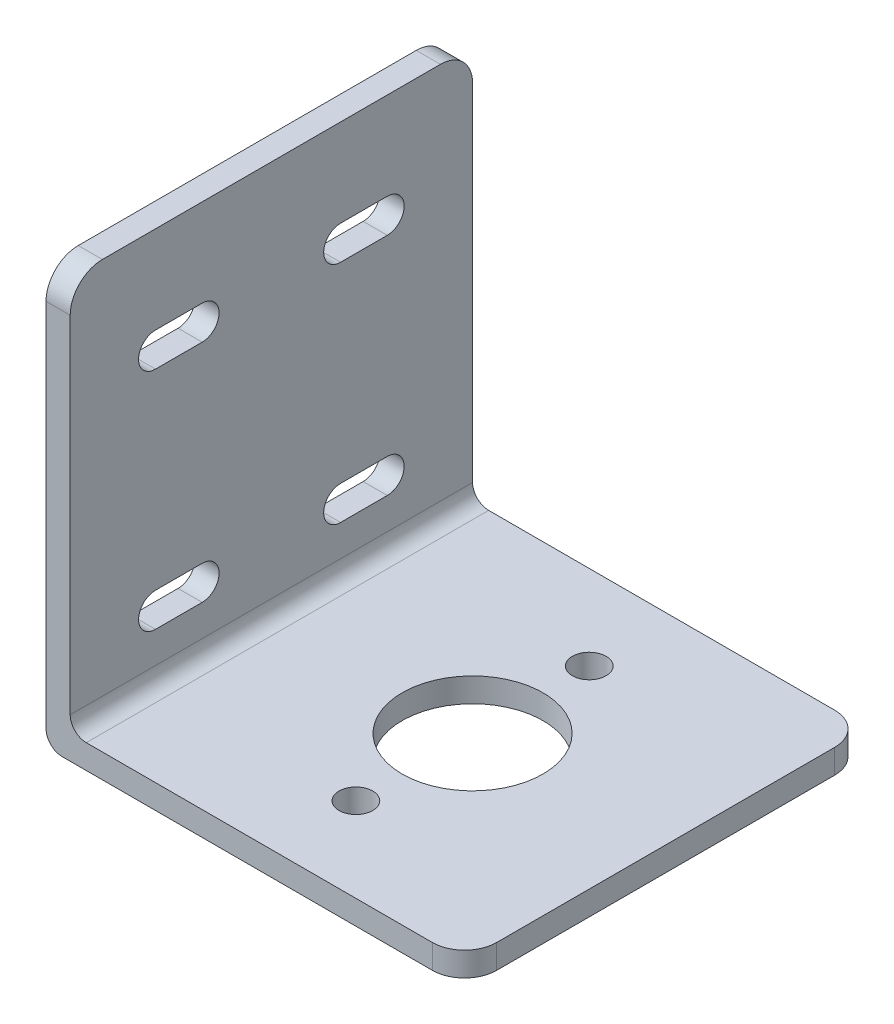
SolidWorks part; units mm, degrees
ref_plane "Спереди" through (0, 0, 0) normal (0, 0, 1) x (1, 0, 0)
ref_plane "Сверху" through (0, 0, 0) normal (0, 1, 0) x (1, 0, 0)
ref_plane "Справа" through (0, 0, 0) normal (1, 0, 0) x (0, 0, -1)
sketch "Эскиз1" plane through (0, 0, 0) normal (0, 1, 0) x (1, 0, 0)
  line L0 (28, 50) -> (28, 0) construction
  line L1 (0, 0) -> (52, 0)
  line L2 (0, 0) -> (0, 50)
  line L3 (0, 50) -> (52, 50)
  line L4 (52, 0) -> (52, 50)
  circle A0 centre (28, 39.5) radius 2.1
  circle A1 centre (28, 10.5) radius 2.1
  circle A2 centre (28, 25) radius 8.75
  dimension "D6" = 17.5
  dimension "D7" = 4.2
  dimension "D8" = 4.2
  dimension "D1" = 50
  dimension "D2" = 52
  dimension "D3" = 28
  dimension "D4" = 29
  dimension "D5" = 14.5
extrude "Бобышка-Вытянуть1" add sketch "Эскиз1" along normal blind 3
sketch "Эскиз2" plane through (0, 3, 0) normal (0, 1, 0) x (1, 0, 0)
  line L0 (0, 0) -> (52, 0) construction
  line L1 (0, 50) -> (3, 50)
  line L2 (0, 50) -> (0, 0)
  line L3 (0, 0) -> (3, 0)
  line L4 (3, 50) -> (3, 0)
  dimension "D1" = 3
extrude "Бобышка-Вытянуть2" add sketch "Эскиз2" along normal blind 49
sketch "Эскиз3" plane through (0, 0, 0) normal (-1, 0, 0) x (0, 0, 1)
  line L0 (-50, 39) -> (0, 39) construction
  line L1 (-50, 52) -> (-50, 0) construction
  line L2 (0, 52) -> (0, 0) construction
  line L3 (-50, 11) -> (0, 11) construction
  line L4 (-50, 0) -> (0, 0) construction
  line L5 (-36.5, 13.1) -> (-36.5, 8.9) construction
  line L6 (-39.4, 13.1) -> (-33.6, 13.1)
  line L7 (-16.4, 13.1) -> (-10.6, 13.1)
  line L8 (-39.4, 8.9) -> (-33.6, 8.9)
  line L9 (-16.4, 8.9) -> (-10.6, 8.9)
  line L10 (-16.4, 41.1) -> (-10.6, 41.1)
  line L11 (-16.4, 36.9) -> (-10.6, 36.9)
  line L12 (-39.4, 41.1) -> (-33.6, 41.1)
  line L13 (-39.4, 36.9) -> (-33.6, 36.9)
  line L14 (-13.5, 13.1) -> (-13.5, 8.9) construction
  arc A0 (-39.4, 13.1) -> (-39.4, 8.9) centre (-39.4, 11) ccw
  arc A1 (-33.6, 8.9) -> (-33.6, 13.1) centre (-33.6, 11) ccw
  arc A2 (-16.4, 13.1) -> (-16.4, 8.9) centre (-16.4, 11) ccw
  arc A3 (-10.6, 8.9) -> (-10.6, 13.1) centre (-10.6, 11) ccw
  arc A4 (-16.4, 41.1) -> (-16.4, 36.9) centre (-16.4, 39) ccw
  arc A5 (-10.6, 36.9) -> (-10.6, 41.1) centre (-10.6, 39) ccw
  arc A6 (-39.4, 41.1) -> (-39.4, 36.9) centre (-39.4, 39) ccw
  arc A7 (-33.6, 36.9) -> (-33.6, 41.1) centre (-33.6, 39) ccw
  dimension "D6" = 2.1
  dimension "D7" = 2.1
  dimension "D1" = 28
  dimension "D2" = 11
  dimension "D3" = 5.8
  dimension "D4" = 4.2
  dimension "D5" = 2.1
  dimension "D8" = 13.5
  dimension "D9" = 2
  dimension "D11" = 23
  dimension "D10" = 2
extrude "Вырез-Вытянуть1" cut sketch "Эскиз3" against normal blind 4
fillet "Скругление1" radius 2 1 edges
fillet "Скругление2" radius 2 1 edges at (0, 0, -25)
fillet "Скругление3" radius 4 1 edges at (1.5, 52, 0)
fillet "Скругление4" radius 4 1 edges at (1.5, 52, -50)
fillet "Скругление5" radius 4 1 edges at (52, 1.5, 0)
fillet "Скругление6" radius 4 1 edges at (52, 1.5, -50)
